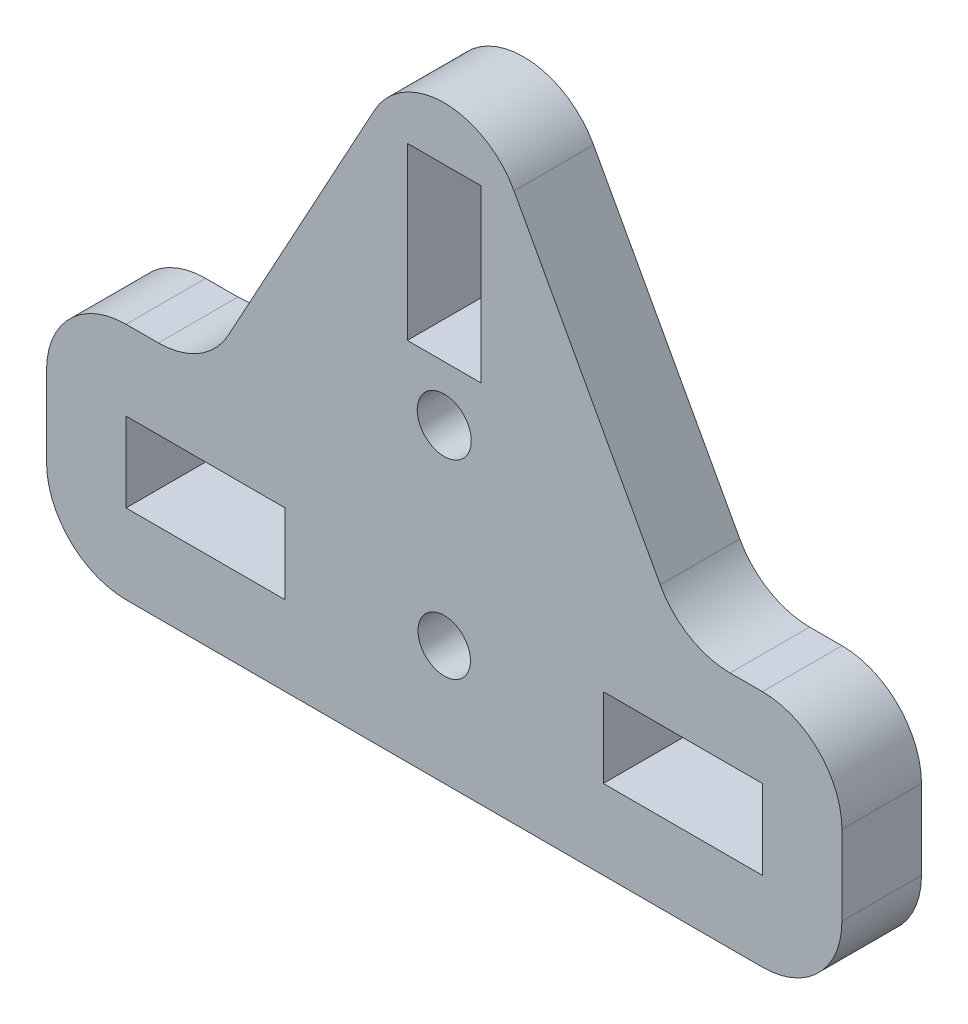
SolidWorks part; units mm, degrees
ref_plane "Front Plane" through (0, 0, 0) normal (0, 0, 1) x (1, 0, 0)
ref_plane "Top Plane" through (0, 0, 0) normal (0, 1, 0) x (1, 0, 0)
ref_plane "Right Plane" through (0, 0, 0) normal (1, 0, 0) x (0, 0, -1)
sketch "Sketch1" plane through (0, 0, 0) normal (0, 0, 1) x (1, 0, 0)
  line L1 (-31.75, -9.525) -> (31.75, -9.525)
  line L2 (-31.75, -9.525) -> (-31.75, 9.525)
  line L3 (-31.75, 9.525) -> (31.75, 9.525)
  line L4 (31.75, -9.525) -> (31.75, 9.525)
  line L5 (-31.75, -9.525) -> (31.75, 9.525) construction
  line L6 (-31.75, 9.525) -> (31.75, -9.525) construction
  point P0 (0, 0)
  dimension "D1" = 19.05
  dimension "D2" = 63.5
extrude "Boss-Extrude1" add sketch "Sketch1" along normal blind 6.35
sketch "Sketch2" plane through (0, 0, 6.35) normal (0, 0, 1) x (1, 0, 0)
  line L0 (0, 3.175) -> (0, -3.175) construction
  line L1 (-31.75, -9.525) -> (31.75, -9.525) construction
  line L2 (-31.75, -3.175) -> (31.75, -3.175) construction
  line L3 (-31.75, 9.525) -> (-31.75, -9.525) construction
  line L4 (31.75, -9.525) -> (31.75, 9.525) construction
  line L5 (-31.75, 3.175) -> (31.75, 3.175) construction
  line L7 (-25.4, 3.175) -> (-12.7, 3.175)
  line L8 (-25.4, 3.175) -> (-25.4, -3.175)
  line L9 (-25.4, -3.175) -> (-12.7, -3.175)
  line L10 (-12.7, 3.175) -> (-12.7, -3.175)
  line L11 (12.7, 3.175) -> (25.4, 3.175)
  line L12 (12.7, 3.175) -> (12.7, -3.175)
  line L13 (12.7, -3.175) -> (25.4, -3.175)
  line L14 (25.4, 3.175) -> (25.4, -3.175)
  circle A0 centre (0, 0) radius 2.0955
  dimension "D3" = 4.191
  dimension "D1" = 6.35
  dimension "D2" = 6.35
  dimension "D4" = 12.7
  dimension "D5" = 12.7
  dimension "D6" = 12.7
  dimension "D7" = 12.7
extrude "Cut-Extrude1" cut sketch "Sketch2" against normal blind 6.35
sketch "Sketch3" plane through (0, 0, 6.35) normal (0, 0, 1) x (1, 0, 0)
  line L0 (0, 0) -> (0, 44.45) construction
  line L1 (0, 9.525) -> (-19.05, 9.525)
  line L2 (31.75, 9.525) -> (-31.75, 9.525) construction
  line L3 (-19.05, 9.525) -> (0, 44.45)
  line L4 (0, 44.45) -> (19.05, 9.525)
  line L5 (0, 44.45) -> (0, 9.525)
  line L6 (19.05, 9.525) -> (0, 9.525)
  circle A0 centre (0, 31.1891) radius 6.35
  line M11 (31.75, 9.525) -> (-31.75, 9.525)
  dimension "D3" = 12.7
  dimension "D1" = 34.925
  dimension "D2" = 19.05
extrude "Boss-Extrude2" add sketch "Sketch3" against normal blind 6.35 contours A0 L3 L5 M11 | L5 A0 | A0 L5 | A0 L5 L4 M11
sketch "Sketch4" plane through (0, 0, 0) normal (0, 0, -1) x (-1, 0, 0)
  line L4 (-2.9464, 19.6364) -> (2.9464, 19.6364)
  line L5 (2.9464, 19.6364) -> (2.9464, 33.2635)
  line L6 (2.9464, 33.2635) -> (-2.9464, 33.2635)
  line L7 (-2.9464, 33.2635) -> (-2.9464, 19.6364)
  line L8 (-2.9464, 19.6364) -> (2.9464, 19.6364)
  line L9 (2.9464, 19.6364) -> (2.9464, 33.2635)
  line L10 (2.9464, 33.2635) -> (-2.9464, 33.2635)
  line L11 (-2.9464, 33.2635) -> (-2.9464, 19.6364)
  circle A0 centre (0, 15.24) radius 2.159 construction
  circle A1 centre (0, 15.24) radius 2.159
  dimension "D1" = 0
extrude "Cut-Extrude3" cut sketch "Sketch4" against normal blind 6.35
fillet "Fillet1" radius 6.35 6 edges at (31.75, -9.525, 3.175) (31.75, 9.525, 3.175) (-31.75, -9.525, 3.175) (-31.75, 9.525, 3.175)
